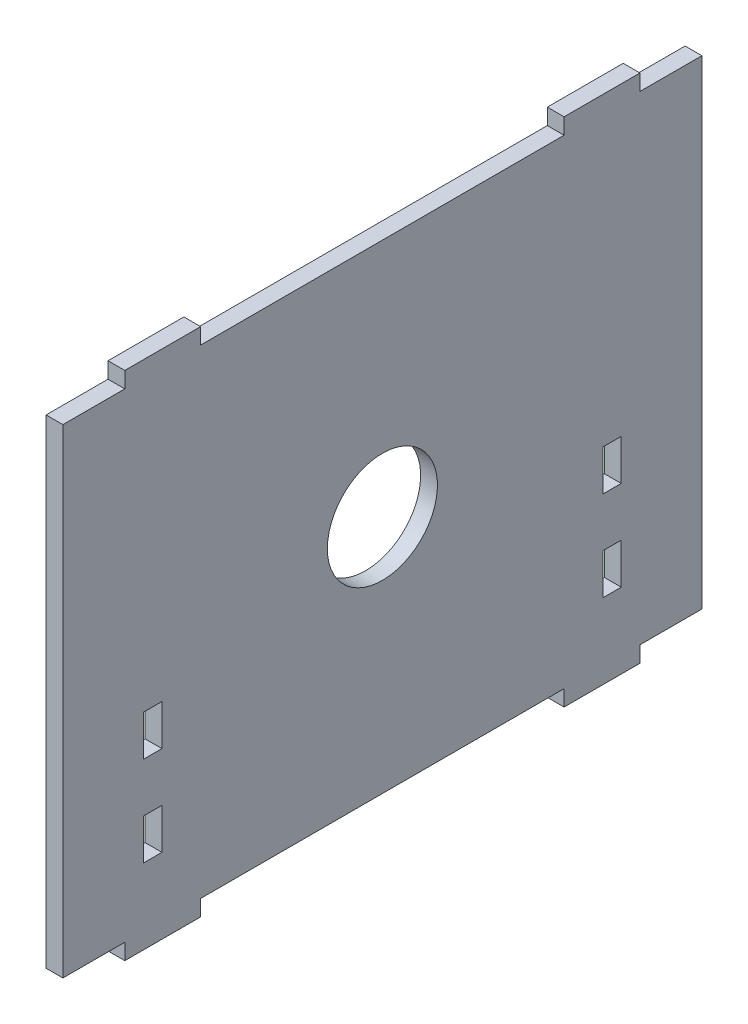
SolidWorks part; units mm, degrees
ref_plane "Front" through (0, 0, 0) normal (0, 0, 1) x (1, 0, 0)
ref_plane "Top" through (0, 0, 0) normal (0, 1, 0) x (1, 0, 0)
ref_plane "Right" through (0, 0, 0) normal (1, 0, 0) x (0, 0, -1)
sketch "Sketch1" plane through (0, 0, 0) normal (1, 0, 0) x (0, 0, -1)
  line L1 (-101.6, 0) -> (101.6, 0)
  line L2 (-101.6, 0) -> (-101.6, 152.4)
  line L3 (-101.6, 152.4) -> (101.6, 152.4)
  line L4 (101.6, 0) -> (101.6, 152.4)
  point P4 (0, 0)
  dimension "D1" = 203.2
  dimension "D2" = 152.4
extrude "Boss-Extrude2" add sketch "Sketch1" along normal blind 5.334
sketch "Sketch2" plane through (0, 0, 0) normal (-1, 0, 0) x (0, 0, 1)
  line L0 (101.6, 152.4) -> (101.6, 0) construction
  circle A0 centre (0, 76.2) radius 17.5
  point P6 (101.6, 76.2)
  dimension "D2" = 35
extrude "Cut-Extrude1" cut sketch "Sketch2" against normal through all
sketch "Sketch3" plane through (0, 0, 0) normal (-1, 0, 0) x (0, 0, 1)
  line L0 (101.6, 0) -> (-101.6, 0) construction
  line L1 (57.785, 0) -> (81.915, 0)
  line L2 (57.785, 0) -> (57.785, -5.08)
  line L3 (57.785, -5.08) -> (81.915, -5.08)
  line L4 (81.915, 0) -> (81.915, -5.08)
  line L5 (101.6, 152.4) -> (101.6, 0) construction
  point P8 (69.85, 0)
  dimension "D1" = 24.13
  dimension "D2" = 31.75
  dimension "D3" = 5.08
extrude "Boss-Extrude3" add sketch "Sketch3" against normal through all contours L3 L4 L1 L2
mirror "Mirror1" about plane through (0, 0, 0) normal (0, 0, 1) of "Boss-Extrude3"
sketch "Sketch4" plane through (0, 0, 0) normal (-1, 0, 0) x (0, 0, 1)
  line L0 (101.6, 0) -> (81.915, 0) construction
  line L1 (70.104, 60.3885) -> (75.946, 60.3885)
  line L2 (70.104, 60.3885) -> (70.104, 47.4345)
  line L3 (70.104, 47.4345) -> (75.946, 47.4345)
  line L4 (75.946, 60.3885) -> (75.946, 47.4345)
  line L5 (70.104, 60.3885) -> (75.946, 47.4345) construction
  line L6 (70.104, 47.4345) -> (75.946, 60.3885) construction
  line L7 (70.104, 31.8135) -> (75.946, 31.8135)
  line L8 (70.104, 31.8135) -> (70.104, 18.8595)
  line L9 (70.104, 18.8595) -> (75.946, 18.8595)
  line L10 (75.946, 31.8135) -> (75.946, 18.8595)
  line L11 (70.104, 31.8135) -> (75.946, 18.8595) construction
  line L12 (70.104, 18.8595) -> (75.946, 31.8135) construction
  line L13 (101.6, 152.4) -> (101.6, 0) construction
  point P0 (73.025, 53.9115)
  point P5 (73.025, 25.3365)
  dimension "D1" = 5.842
  dimension "D2" = 12.954
  dimension "D3" = 25.3365
  dimension "D4" = 28.575
  dimension "D5" = 28.575
extrude "Cut-Extrude2" cut sketch "Sketch4" against normal through all
mirror "Mirror2" about plane through (0, 0, 0) normal (0, 0, 1) of "Cut-Extrude2"
ref_plane "Plane1" through (0, 76.2, 0) normal (0, 1, 0) x (1, 0, 0)
mirror "Mirror3" about plane through (0, 76.2, 0) normal (0, 1, 0) of "Mirror1", "Boss-Extrude3"
